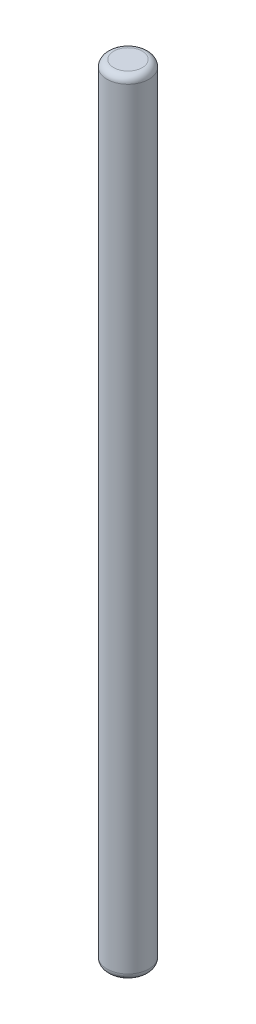
SolidWorks part; units mm, degrees
ref_plane "Front Plane" through (0, 0, 0) normal (0, 0, 1) x (1, 0, 0)
ref_plane "Top Plane" through (0, 0, 0) normal (0, 1, 0) x (1, 0, 0)
ref_plane "Right Plane" through (0, 0, 0) normal (1, 0, 0) x (0, 0, -1)
sketch "Sketch1" plane through (0, 0, 0) normal (0, 1, 0) x (1, 0, 0)
  circle A0 centre (0, 0) radius 2.3813
  dimension "D1" = 4.7625
extrude "Boss-Extrude1" add sketch "Sketch1" along normal blind 88.9
fillet "Fillet1" radius 0.762 2 edges at (0, 0, 2.3813) (0, 88.9, 2.3813)
